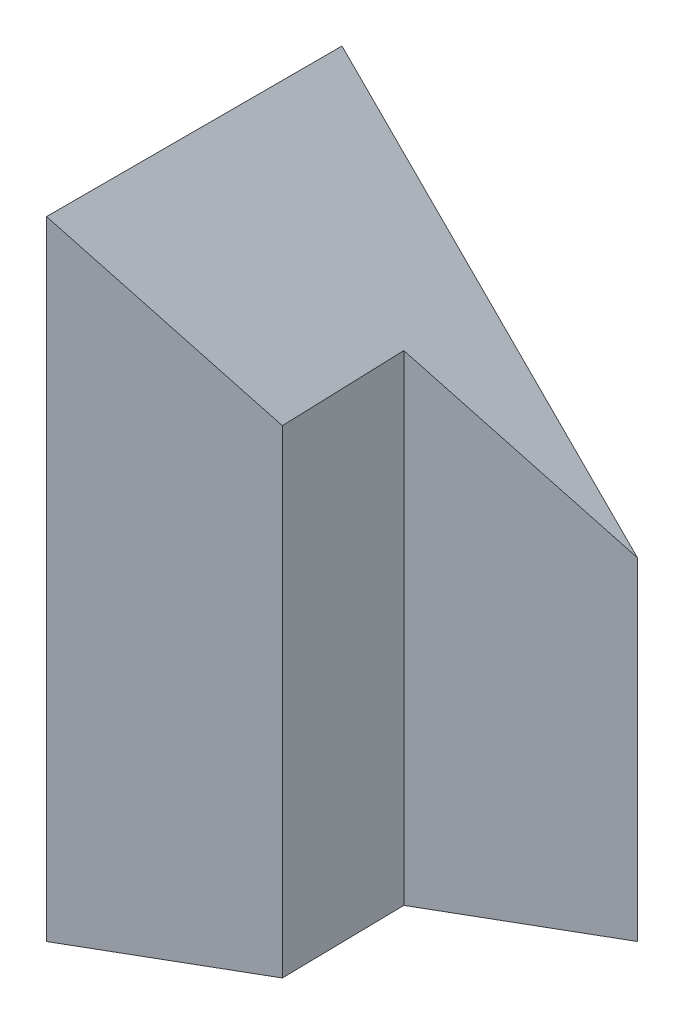
SolidWorks part; units mm, degrees
ref_plane "Front Plane" through (0, 0, 0) normal (0, 0, 1) x (1, 0, 0)
ref_plane "Top Plane" through (0, 0, 0) normal (0, 1, 0) x (1, 0, 0)
ref_plane "Right Plane" through (0, 0, 0) normal (1, 0, 0) x (0, 0, -1)
sketch "Sketch1" plane through (0, 0, 0) normal (0, 1, 0) x (1, 0, 0)
  line L0 (25.094, 18.591) -> (-25.706, 18.591)
  line L1 (-25.706, 18.591) -> (-25.706, -32.209)
  line L2 (-25.706, -32.209) -> (0.0003, -17.3675)
  line L3 (0.0003, -17.3675) -> (-0.3708, 3.8889)
  line L4 (-0.3708, 3.8889) -> (25.094, 18.591)
  dimension "D1" = 50.8
  dimension "D2" = 50.8
  dimension "D3" = 60
  dimension "D4" = 30
  dimension "D5" = 1
extrude "Boss-Extrude1" add sketch "Sketch1" along normal blind 107.95
sketch "Sketch2" plane through (0, 0, 0) normal (0, 0, 1) x (1, 0, 0)
  line L0 (-25.706, 107.95) -> (25.094, 57.15)
  line L1 (25.094, 107.95) -> (25.094, 0) construction
  line L2 (-25.706, 107.95) -> (-25.706, 0) construction
  dimension "D1" = 45
extrude "Cut-Extrude1" cut sketch "Sketch2" against normal through all and the other way through all
